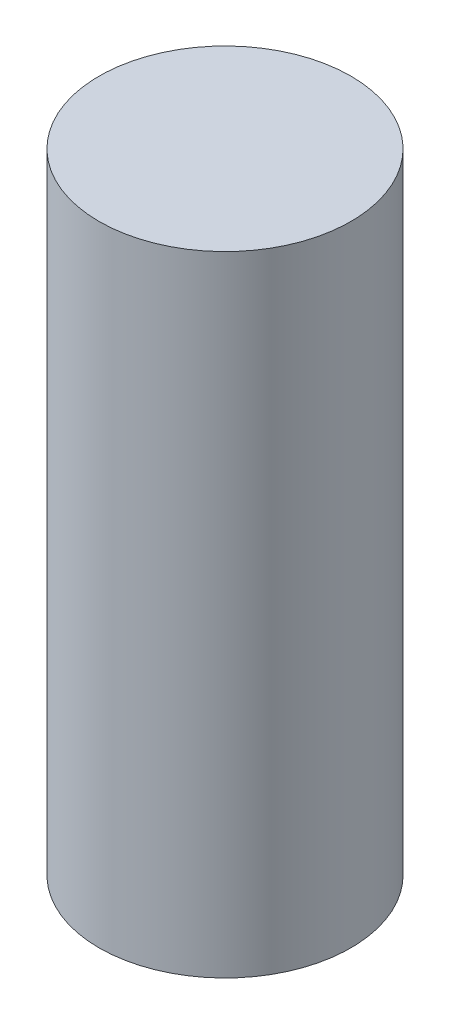
SolidWorks part; units mm, degrees
ref_plane "Front Plane" through (0, 0, 0) normal (0, 0, 1) x (1, 0, 0)
ref_plane "Top Plane" through (0, 0, 0) normal (0, 1, 0) x (1, 0, 0)
ref_plane "Right Plane" through (0, 0, 0) normal (1, 0, 0) x (0, 0, -1)
sketch "Sketch1" plane through (0, 0, 0) normal (0, 1, 0) x (1, 0, 0)
  circle A0 centre (0, 0) radius 50.8381
  dimension "D1" = 101.6762
extrude "Boss-Extrude1" add sketch "Sketch1" along normal blind 254
